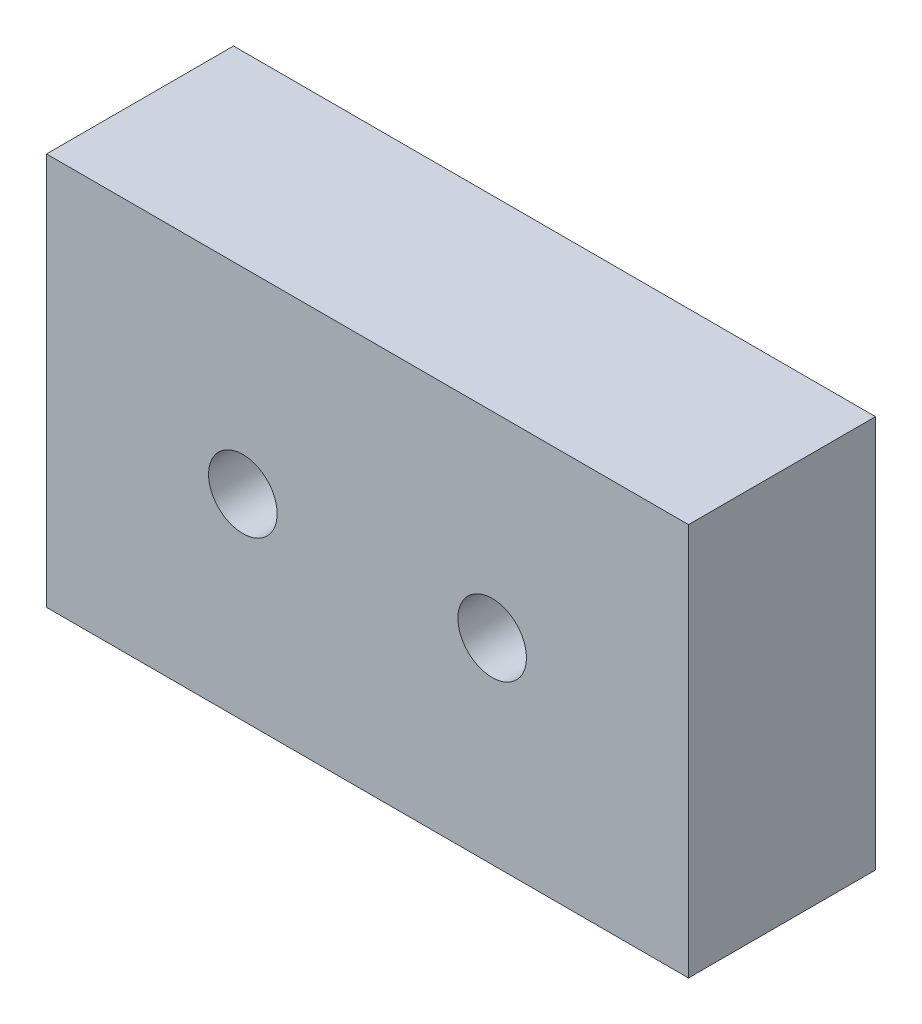
SolidWorks part; units mm, degrees
ref_plane "Plan de face" through (0, 0, 0) normal (0, 0, 1) x (1, 0, 0)
ref_plane "Plan de dessus" through (0, 0, 0) normal (0, 1, 0) x (1, 0, 0)
ref_plane "Plan de droite" through (0, 0, 0) normal (1, 0, 0) x (0, 0, -1)
sketch "Esquisse1" plane through (0, 0, 0) normal (0, 0, 1) x (1, 0, 0)
  line L1 (-20.6, 12.6) -> (20.6, 12.6)
  line L2 (-20.6, 12.6) -> (-20.6, -12.6)
  line L3 (-20.6, -12.6) -> (20.6, -12.6)
  line L4 (20.6, 12.6) -> (20.6, -12.6)
  line L5 (-20.6, 12.6) -> (20.6, -12.6) construction
  line L6 (-20.6, -12.6) -> (20.6, 12.6) construction
  point P0 (0, 0)
  dimension "D1" = 25.2
  dimension "D2" = 41.2
extrude "Boss.-Extru.1" add sketch "Esquisse1" along normal blind 12
sketch "Esquisse2" plane through (0, 0, 0) normal (0, 0, 1) x (1, 0, 0)
  line L0 (-8, 0) -> (8, 0) construction
  circle A0 centre (8, 0) radius 2.2
  circle A1 centre (-8, 0) radius 2.2
  point P4 (0, 0)
  dimension "D2" = 4.4
  dimension "D1" = 16
extrude "Enlèv. mat.-Extru.1" cut sketch "Esquisse2" along normal blind 12
ref_plane "Plan1" through (0, 0, 21) normal (0, 0, 1) x (1, 0, 0)
ref_plane "Plan2" through (0, -1.27, 0) normal (0, 1, 0) x (1, 0, 0)
